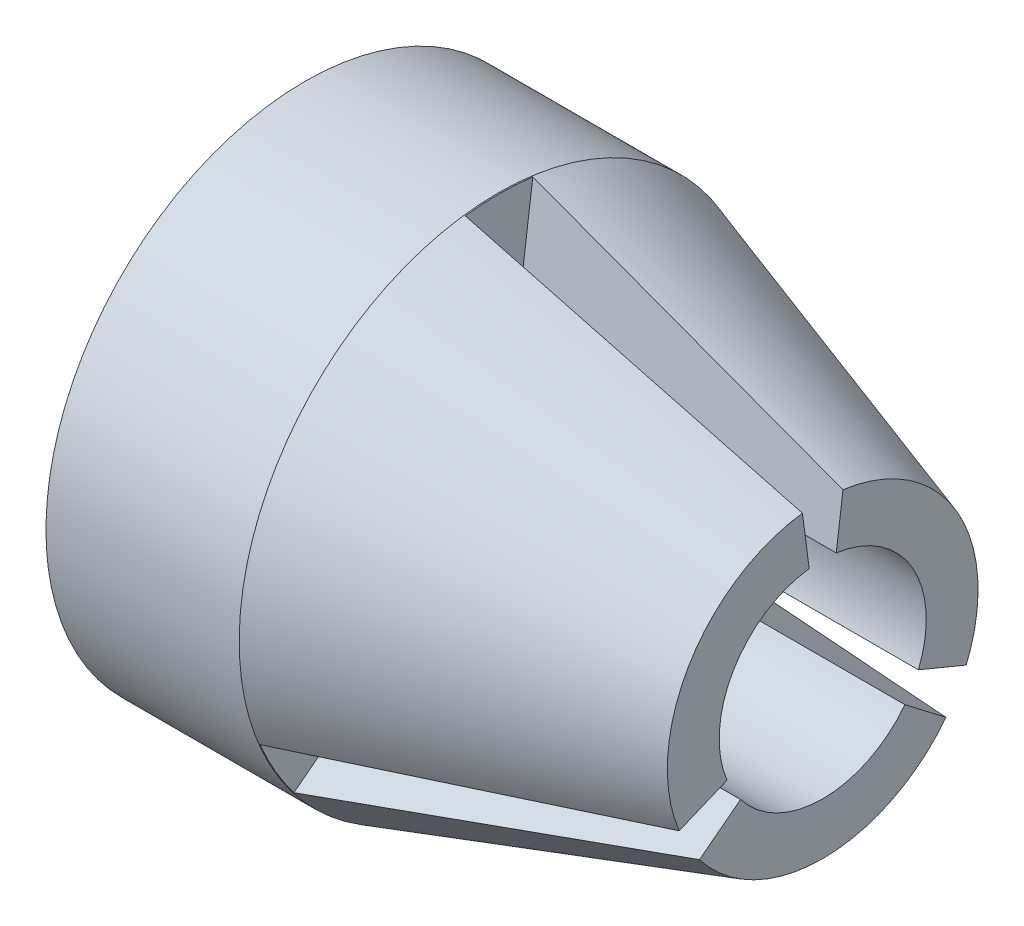
SolidWorks part; units mm, degrees
ref_plane "Front Plane" through (0, 0, 0) normal (0, 0, 1) x (1, 0, 0)
ref_plane "Top Plane" through (0, 0, 0) normal (0, 1, 0) x (1, 0, 0)
ref_plane "Right Plane" through (0, 0, 0) normal (1, 0, 0) x (0, 0, -1)
sketch "Sketch1" plane through (0, 0, 0) normal (0, 0, 1) x (1, 0, 0)
  line L0 (0, 0) -> (0, 5)
  line L1 (0, 5) -> (3.7315, 5)
  line L2 (3.7315, 5) -> (10, 3)
  line L3 (10, 3) -> (10, 0)
  line L4 (10, 0) -> (0, 0)
  dimension "D1" = 3
  dimension "D2" = 5
  dimension "D3" = 10
revolve "Revolve1" add sketch "Sketch1" angle 360 about L4
sketch "Sketch3" plane through (10, 0, 0) normal (1, 0, 0) x (0, 0, -1)
  circle A0 centre (0, 0) radius 2
  dimension "D1" = 4
extrude "Cut-Extrude1" cut sketch "Sketch3" against normal blind 5
sketch "Sketch4" plane through (0, 0, 0) normal (-1, 0, 0) x (0, 0, 1)
  circle A0 centre (0, 0) radius 1
  dimension "D1" = 2
extrude "Cut-Extrude2" cut sketch "Sketch4" against normal blind 5
sketch "Sketch5" plane through (10, 0, 0) normal (1, 0, 0) x (0, 0, -1)
  line L0 (0, 0) -> (0, 5) construction
  line L1 (0, 0) -> (0.6526, 4.9572)
  line L2 (0, 0) -> (-0.6526, 4.9572)
  line L3 (0, 0) -> (3.9668, -3.0438)
  line L4 (0, 0) -> (4.6194, -1.9134)
  line L5 (0, 0) -> (-4.6194, -1.9134)
  line L6 (0, 0) -> (-3.9668, -3.0438)
  circle A0 centre (0, 0) radius 5 construction
  arc A1 (0.6526, 4.9572) -> (-0.6526, 4.9572) centre (0, 0) ccw
  arc A2 (-0.6526, 4.9572) -> (0.6526, 4.9572) centre (0, 0) cw
  arc A3 (4.6194, -1.9134) -> (3.9668, -3.0438) centre (0, 0) cw
  arc A4 (-3.9668, -3.0438) -> (-4.6194, -1.9134) centre (0, 0) cw
  point P16 (0, 0)
  circle M6 centre (0, 0) radius 2
  circle M7 centre (0, 0) radius 3
  dimension "D1" = 7.5
  dimension "D2" = 15
  dimension "D3" = 3
extrude "Cut-Extrude3" cut sketch "Sketch5" against normal blind 6.25 contours L0 A2 L2 M7 | L0 L1 A1 M7 | L0 L1 M6 M7 | L0 L2 M6 M7 | L2 L0 M6 | L0 L1 M6 | A3 L4 L3 M7 | L4 L3 M6 M7 | L5 A4 L6
